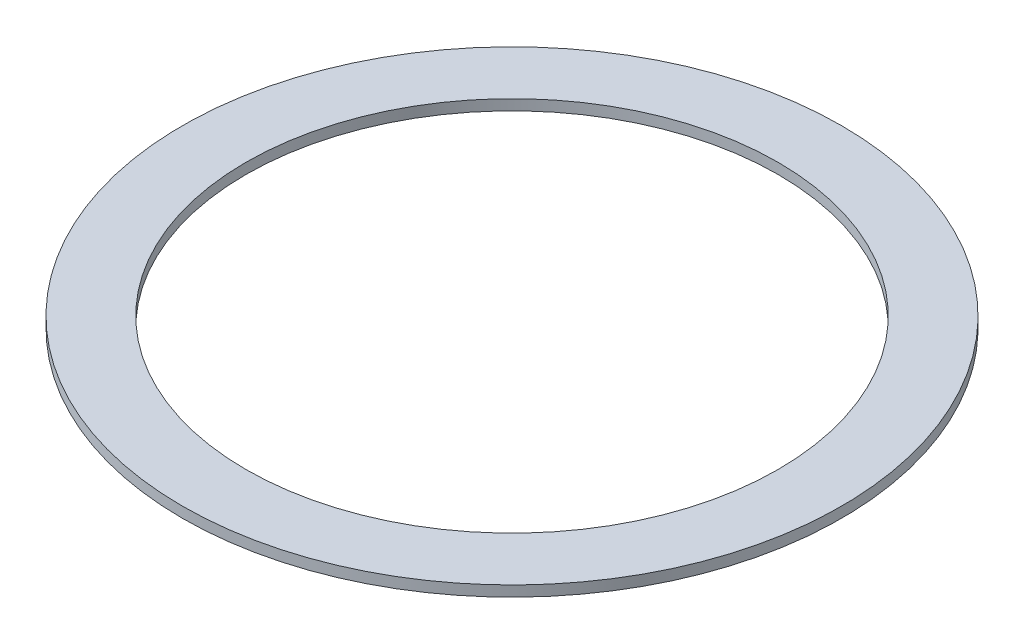
SolidWorks part; units mm, degrees
ref_plane "Front Plane" through (0, 0, 0) normal (0, 0, 1) x (1, 0, 0)
ref_plane "Top Plane" through (0, 0, 0) normal (0, 1, 0) x (1, 0, 0)
ref_plane "Right Plane" through (0, 0, 0) normal (1, 0, 0) x (0, 0, -1)
sketch "Sketch1" plane through (0, 0, 0) normal (0, 1, 0) x (1, 0, 0)
  circle A0 centre (0, 0) radius 7.9121
  dimension "OD" = 15.8242
extrude "Boss-Extrude1" add sketch "Sketch1" along normal blind 0.254
sketch "Sketch5" plane through (0, 0.254, 0) normal (0, 1, 0) x (-1, 0, 0)
  circle A0 centre (0, 0) radius 6.3881
  dimension "ID" = 12.7762
extrude "Cut-Extrude1" cut sketch "Sketch5" against normal through all
